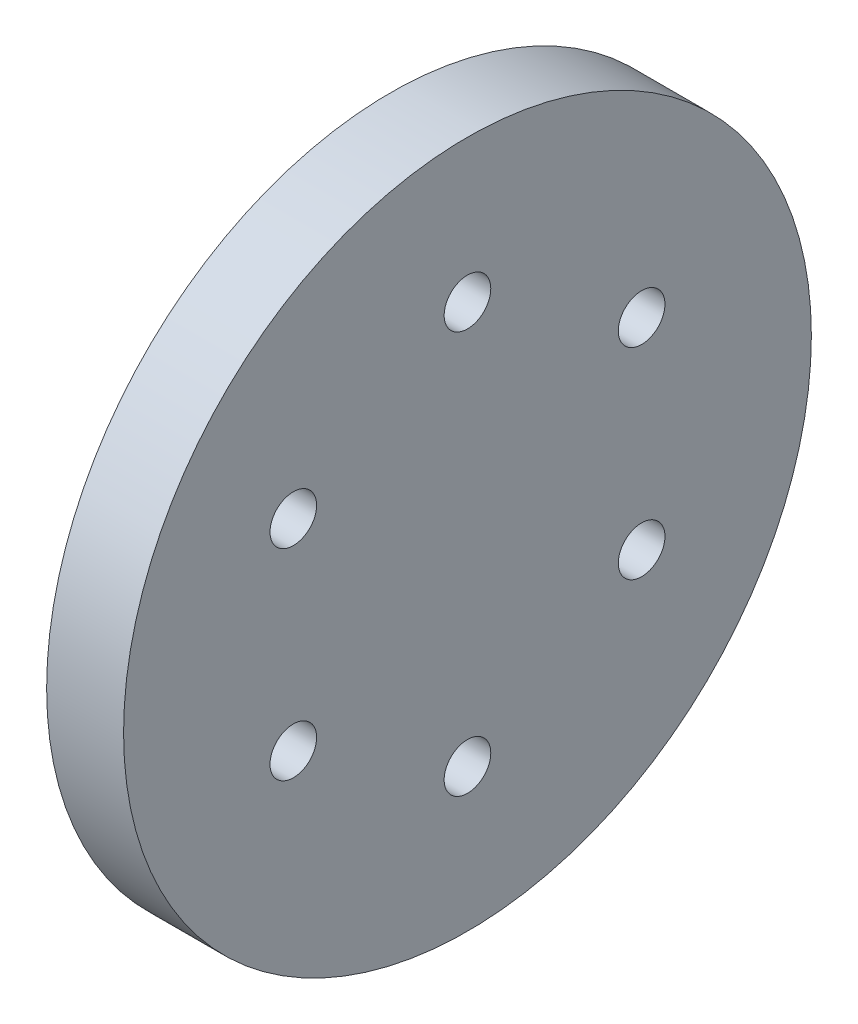
SolidWorks part; units mm, degrees
ref_plane "前视基准面" through (0, 0, 0) normal (0, 0, 1) x (1, 0, 0)
ref_plane "上视基准面" through (0, 0, 0) normal (0, 1, 0) x (1, 0, 0)
ref_plane "右视基准面" through (0, 0, 0) normal (1, 0, 0) x (0, 0, -1)
sketch "草图1" plane through (0, 0, 0) normal (1, 0, 0) x (0, 0, -1)
  circle A0 centre (0, 0) radius 29.5
  dimension "D1" = 59
extrude "凸台-拉伸1" add sketch "草图1" along normal blind 6.6
sketch "草图2" plane through (6.6, 0, 0) normal (1, 0, 0) x (0, 0, -1)
  circle A0 centre (0, 0) radius 17.25 construction
  circle A1 centre (0, 17.25) radius 2
  circle A2 centre (14.9389, 8.625) radius 2
  circle A3 centre (14.9389, -8.625) radius 2
  circle A4 centre (0, -17.25) radius 2
  circle A5 centre (-14.9389, -8.625) radius 2
  circle A6 centre (-14.9389, 8.625) radius 2
  point P17 (0, 0)
  dimension "D1" = 34.5
  dimension "D2" = 6
extrude "切除-拉伸1" cut sketch "草图2" against normal blind 21
